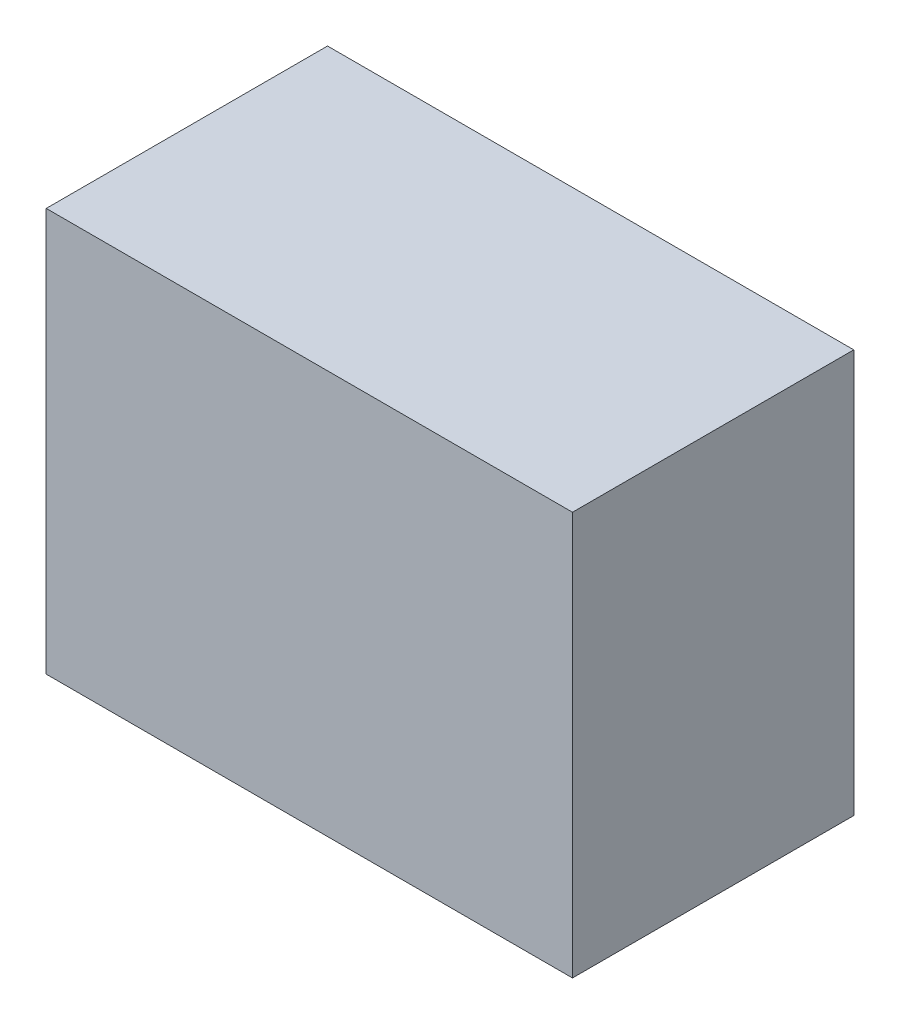
SolidWorks part; units mm, degrees
ref_plane "Front Plane" through (0, 0, 0) normal (0, 0, 1) x (1, 0, 0)
ref_plane "Top Plane" through (0, 0, 0) normal (0, 1, 0) x (1, 0, 0)
ref_plane "Right Plane" through (0, 0, 0) normal (1, 0, 0) x (0, 0, -1)
sketch "Sketch1" plane through (0, 0, 0) normal (0, 0, 1) x (1, 0, 0)
  line L1 (-49.25, -37.75) -> (49.25, -37.75)
  line L2 (-49.25, -37.75) -> (-49.25, 37.75)
  line L3 (-49.25, 37.75) -> (49.25, 37.75)
  line L4 (49.25, -37.75) -> (49.25, 37.75)
  line L5 (-49.25, -37.75) -> (49.25, 37.75) construction
  line L6 (-49.25, 37.75) -> (49.25, -37.75) construction
  point P0 (0, 0)
  dimension "D1" = 98.5
  dimension "D2" = 75.5
extrude "Boss-Extrude1" add sketch "Sketch1" along normal blind 52.65
sketch "Sketch2" plane through (0, 0, 0) normal (0, 0, -1) x (-1, 0, 0)
  line L1 (41.5, 30) -> (-41.5, 30) construction
  line L2 (41.5, 30) -> (41.5, -30) construction
  line L3 (41.5, -30) -> (-41.5, -30) construction
  line L4 (-41.5, 30) -> (-41.5, -30) construction
  line L5 (41.5, 30) -> (-41.5, -30) construction
  line L6 (41.5, -30) -> (-41.5, 30) construction
  circle A0 centre (-41.5, 30) radius 3.4
  circle A1 centre (-41.5, -30) radius 3.4
  circle A2 centre (41.5, 30) radius 3.4
  circle A3 centre (41.5, -30) radius 3.4
  point P0 (0, 0)
  dimension "D3" = 6.8
  dimension "D1" = 83
  dimension "D2" = 60
extrude "Cut-Extrude1" cut sketch "Sketch2" against normal blind 6.35
